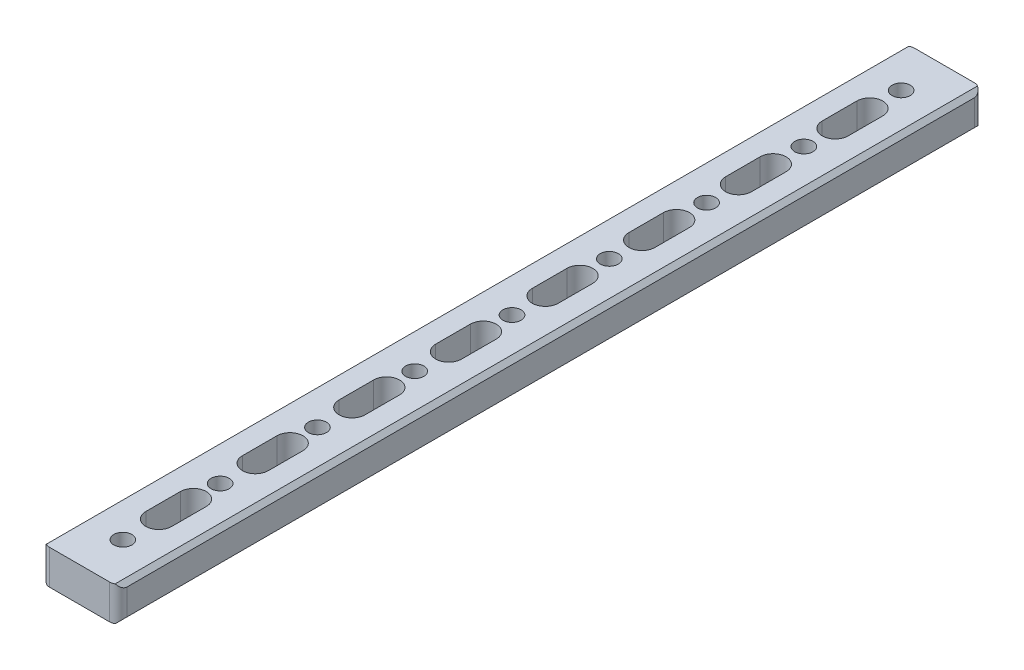
SolidWorks part; units mm, degrees
material "1060 合金"
ref_plane "前视基准面" through (0, 0, 0) normal (0, 0, 1) x (1, 0, 0)
ref_plane "上视基准面" through (0, 0, 0) normal (0, 1, 0) x (1, 0, 0)
ref_plane "右视基准面" through (0, 0, 0) normal (1, 0, 0) x (0, 0, -1)
other "Configuration Table"
sketch "草图1" plane through (0, 0, 0) normal (0, 0, 1) x (1, 0, 0)
  line L1 (-8.95, -4) -> (8.95, -4)
  line L2 (-8.95, -4) -> (-8.95, 4)
  line L3 (-8.95, 4) -> (8.95, 4)
  line L4 (8.95, -4) -> (8.95, 4)
  line L5 (-8.95, -4) -> (8.95, 4) construction
  line L6 (-8.95, 4) -> (8.95, -4) construction
  point P0 (0, 0)
  dimension "D1" = 17.9
  dimension "D2" = 8
extrude "凸台-拉伸1" add sketch "草图1" along normal mid plane 200
sketch "草图2" plane through (0, 4, 0) normal (0, 1, 0) x (1, 0, 0)
  line L0 (0, 90) -> (0, -90) construction
  circle A0 centre (0, 90) radius 1.5
  circle A1 centre (0, 45) radius 1.5
  circle A2 centre (0, 0) radius 1.5
  circle A3 centre (0, -45) radius 1.5
  circle A4 centre (0, -90) radius 1.5
  point P4 (0, 0)
  dimension "D1" = 5
  dimension "D2" = 45
  dimension "D3" = 3
extrude "切除-拉伸1" cut sketch "草图2" against normal mid plane 200
hole_wizard "M5 螺纹孔1" positions "草图3" profile "草图4" tap size "M5" standard "GB"
sketch "草图3" plane through (0, 4, 0) normal (0, 1, 0) x (1, 0, 0)
  point P0 (0, 90)
  point P3 (0, 45)
  point P6 (0, 0)
  point P9 (0, -45)
  point P12 (0, -90)
sketch "草图4" plane through (0, 4, -90) normal (1, 0, 0) x (0, 0, 1)
  line L0 (0, 0) -> (0, 13.6618)
  line L1 (0, 13.6618) -> (2.1, 12.4)
  line L2 (2.1, 12.4) -> (2.1, 0)
  line L5 (2.1, 0) -> (0, 0)
  line L10 (0, 13.6618) -> (-2.1, 12.4) construction
  line L11 (0, -6.35) -> (0, 107.95) construction
  dimension "螺纹孔钻头直径" = 4.2
  dimension "螺纹孔钻头深度" = 12.4
  dimension "导头角度" = 118
cosmetic thread "孔螺蚊线1" parameters "D1"=10, "D2"=5
cosmetic thread "孔螺蚊线2" parameters "D1"=10, "D2"=5
cosmetic thread "孔螺蚊线3" parameters "D1"=10, "D2"=5
cosmetic thread "孔螺蚊线4" parameters "D1"=10, "D2"=5
cosmetic thread "孔螺蚊线5" parameters "D1"=10, "D2"=5
chamfer "倒角1" distance 1 angle 45 4 edges at (-8.95, -4, 0) (8.95, -4, 0) (-8.95, 4, 0) (8.95, 4, 0)
fillet "圆角1" radius 2 4 edges at (8.95, 0, -100) (-8.95, 0, -100) (-8.95, 0, 100) (8.95, 0, 100)
sketch "草图5" plane through (0, 4, 0) normal (0, 1, 0) x (1, 0, 0)
  line L0 (0, 90) -> (0, 45) construction
  line L1 (0, 45) -> (0, 0) construction
  line L2 (0, 0) -> (0, -45) construction
  line L3 (0, -45) -> (0, -90) construction
  point P4 (0, 67.5)
  point P11 (0, 22.5)
  point P12 (0, -22.5)
  point P13 (0, -67.5)
hole_wizard "M5 螺纹孔2" positions "草图6" profile "草图7" tap size "M5" standard "GB"
sketch "草图6" plane through (0, 4, 0) normal (0, 1, 0) x (1, 0, 0)
  line L0 (0, 90) -> (0, 45) construction
  point P0 (0, 67.5)
  point P4 (0, 22.5)
  point P7 (0, -22.5)
  point P10 (0, -67.5)
sketch "草图7" plane through (0, 4, -67.5) normal (1, 0, 0) x (0, 0, 1)
  line L0 (0, 0) -> (0, 13.6618)
  line L1 (0, 13.6618) -> (2.1, 12.4)
  line L2 (2.1, 12.4) -> (2.1, 0)
  line L5 (2.1, 0) -> (0, 0)
  line L10 (0, 13.6618) -> (-2.1, 12.4) construction
  line L11 (0, -6.35) -> (0, 107.95) construction
  dimension "螺纹孔钻头直径" = 4.2
  dimension "螺纹孔钻头深度" = 12.4
  dimension "导头角度" = 118
cosmetic thread "孔螺蚊线6" parameters "D1"=10, "D2"=5
cosmetic thread "孔螺蚊线7" parameters "D1"=10, "D2"=5
cosmetic thread "孔螺蚊线8" parameters "D1"=10, "D2"=5
cosmetic thread "孔螺蚊线9" parameters "D1"=10, "D2"=5
sketch "草图8" plane through (0, 4, 0) normal (0, 1, 0) x (1, 0, 0)
  line L0 (0, 90) -> (0, 67.5) construction
  line L1 (0, 82.75) -> (0, 74.75) construction
  line L2 (3, 82.75) -> (3, 74.75)
  line L3 (-3, 82.75) -> (-3, 74.75)
  line L4 (0, 60.4) -> (0, 52.4) construction
  line L5 (3, 60.4) -> (3, 52.4)
  line L6 (-3, 60.4) -> (-3, 52.4)
  line L7 (0, 38.05) -> (0, 30.05) construction
  line L8 (3, 38.05) -> (3, 30.05)
  line L9 (-3, 38.05) -> (-3, 30.05)
  line L10 (0, 15.7) -> (0, 7.7) construction
  line L11 (3, 15.7) -> (3, 7.7)
  line L12 (-3, 15.7) -> (-3, 7.7)
  line L13 (0, -6.65) -> (0, -14.65) construction
  line L14 (3, -6.65) -> (3, -14.65)
  line L15 (-3, -6.65) -> (-3, -14.65)
  line L16 (0, -29) -> (0, -37) construction
  line L17 (3, -29) -> (3, -37)
  line L18 (-3, -29) -> (-3, -37)
  line L19 (0, -51.35) -> (0, -59.35) construction
  line L20 (3, -51.35) -> (3, -59.35)
  line L21 (-3, -51.35) -> (-3, -59.35)
  line L22 (0, -73.7) -> (0, -81.7) construction
  line L23 (3, -73.7) -> (3, -81.7)
  line L24 (-3, -73.7) -> (-3, -81.7)
  line L25 (0, -65.4) -> (0, -90) construction
  arc A0 (3, 82.75) -> (-3, 82.75) centre (0, 82.75) ccw
  arc A1 (-3, 74.75) -> (3, 74.75) centre (0, 74.75) ccw
  arc A2 (3, 60.4) -> (-3, 60.4) centre (0, 60.4) ccw
  arc A3 (-3, 52.4) -> (3, 52.4) centre (0, 52.4) ccw
  arc A4 (3, 38.05) -> (-3, 38.05) centre (0, 38.05) ccw
  arc A5 (-3, 30.05) -> (3, 30.05) centre (0, 30.05) ccw
  arc A6 (3, 15.7) -> (-3, 15.7) centre (0, 15.7) ccw
  arc A7 (-3, 7.7) -> (3, 7.7) centre (0, 7.7) ccw
  arc A8 (3, -6.65) -> (-3, -6.65) centre (0, -6.65) ccw
  arc A9 (-3, -14.65) -> (3, -14.65) centre (0, -14.65) ccw
  arc A10 (3, -29) -> (-3, -29) centre (0, -29) ccw
  arc A11 (-3, -37) -> (3, -37) centre (0, -37) ccw
  arc A12 (3, -51.35) -> (-3, -51.35) centre (0, -51.35) ccw
  arc A13 (-3, -59.35) -> (3, -59.35) centre (0, -59.35) ccw
  arc A14 (3, -73.7) -> (-3, -73.7) centre (0, -73.7) ccw
  arc A15 (-3, -81.7) -> (3, -81.7) centre (0, -81.7) ccw
  circle A16 centre (0, -67.5) radius 2.1 construction
  point P6 (0, 78.75)
  point P15 (0, 56.4)
  point P22 (0, 34.05)
  point P29 (0, 11.7)
  point P36 (0, -10.65)
  point P43 (0, -33)
  point P50 (0, -55.35)
  point P57 (0, -77.7)
  point P65 (0, -57.3116)
  point P66 (0, -77.7)
  dimension "D1" = 3
  dimension "D2" = 8
  dimension "D3" = 8
extrude "切除-拉伸2" cut sketch "草图8" against normal blind 10
